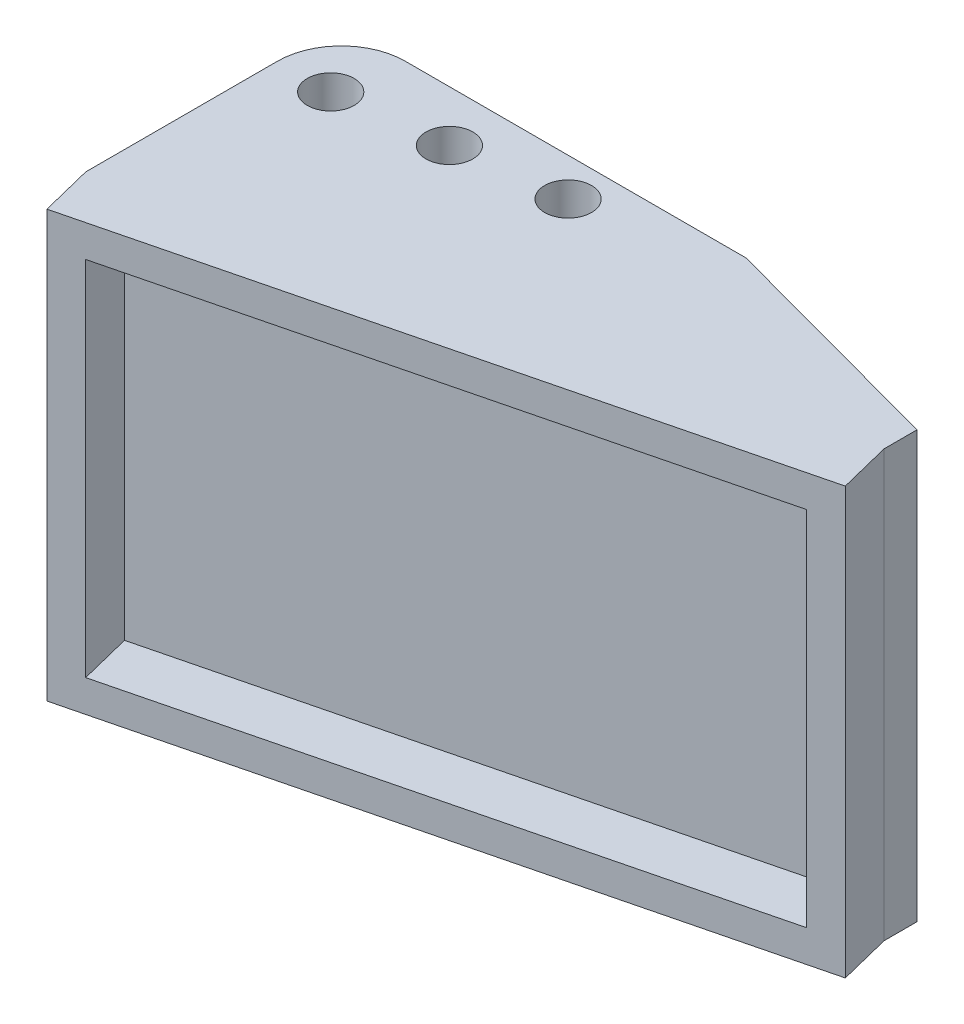
SolidWorks part; units mm, degrees
ref_plane "前视基准面" through (0, 0, 0) normal (0, 0, 1) x (1, 0, 0)
ref_plane "上视基准面" through (0, 0, 0) normal (0, 1, 0) x (1, 0, 0)
ref_plane "右视基准面" through (0, 0, 0) normal (1, 0, 0) x (0, 0, -1)
other "Configuration Table"
sketch "草图1" plane through (0, 0, 0) normal (0, 1, 0) x (1, 0, 0)
  line L0 (-15, -6) -> (15, 1.4798)
  line L1 (-15, 6) -> (15, 6)
  line L2 (-15, 6) -> (-15, -6)
  line L3 (-15, -6) -> (15, -6) construction
  line L4 (15, 6) -> (15, -6) construction
  line L5 (-15, 6) -> (15, -6) construction
  line L6 (-15, -6) -> (15, 6) construction
  line L7 (15, 6) -> (15, 1.4798)
  point P0 (0, 0)
  dimension "D1" = 14
  dimension "D2" = 12
  dimension "D3" = 30
extrude "凸台-拉伸1" add sketch "草图1" along normal blind 20
sketch "草图2" plane through (0, 20, 0) normal (0, 1, 0) x (1, 0, 0)
  line L0 (-15, 6) -> (-15, -6) construction
  line L1 (-12.5, 3) -> (-0.3039, 4.4975) construction
  line L4 (-12.5, 3) -> (-1.0308, 3) construction
  line L5 (15, 6) -> (-15, 6) construction
  circle A1 centre (-12.5, 3) radius 1.1
  circle A2 centre (-7.5373, 3.6093) radius 1.1
  circle A3 centre (-2.5745, 4.2187) radius 1.1
  dimension "D3" = 7
  dimension "D5" = 5
  dimension "D1" = 9
  dimension "D4" = 5
  dimension "D2" = 2.5
sketch "草图3" plane through (0, 0, -6) normal (0, 0, -1) x (-1, 0, 0)
  line L0 (-15, 10) -> (15, 10) construction
  line L1 (-15, 20) -> (-15, 0) construction
  line L2 (15, 20) -> (15, 0) construction
  line L3 (-15, 17.55) -> (15, 17.55)
  line L4 (-15, 2.45) -> (15, 2.45)
  line L5 (-15, 17.55) -> (-15, 2.45)
  line L6 (15, 17.55) -> (15, 2.45)
  dimension "D1" = 7.55
  dimension "D2" = 7.55
extrude "切除-拉伸2" cut sketch "草图2" against normal through all
ref_plane "基准面1" through (0.1676, 0, 0.6724) normal (0.2419, 0, 0.9703) x (0.9703, 0, -0.2419)
extrude "切除-拉伸3" cut sketch "草图3" against normal up to surface (10.4541 mm away) up to plane "基准面1"
fillet "圆角1" radius 3 2 edges at (-15, 1.225, -6) (-15, 18.775, -6)
sketch "草图6" plane through (0.5305, 0, 2.1278) normal (0.2419, 0, 0.9703) x (0.9703, 0, -0.2419)
  line L0 (-14.506, 18.5) -> (-14.506, 1.5)
  line L1 (-14.506, 1.5) -> (13.4124, 1.5)
  line L2 (13.4124, 1.5) -> (13.4124, 18.5)
  line L3 (13.4124, 18.5) -> (-14.506, 18.5)
  line L4 (-16.006, 20) -> (-16.006, 0) construction
  line L5 (14.9124, 20) -> (14.9124, 0) construction
  line L6 (-16.006, 20) -> (14.9124, 20) construction
  line L7 (-16.006, 0) -> (14.9124, 0) construction
  line L9 (-16.006, 20) -> (14.9124, 20)
  line L10 (-16.006, 20) -> (-16.006, 0)
  line L11 (-16.006, 0) -> (14.9124, 0)
  line L12 (14.9124, 20) -> (14.9124, 0)
  dimension "D1" = 1.5
  dimension "D2" = 1.5
  dimension "D3" = 1.5
  dimension "D4" = 1.5
extrude "凸台-拉伸2" add sketch "草图6" along normal blind 2.5
sketch "草图7" plane through (0, 2.45, 0) normal (0, 1, 0) x (1, 0, 0)
  line L0 (15, 3.0258) -> (4, 6)
  line L1 (15, 6) -> (-12, 6) construction
  line L2 (4, 6) -> (15, 6)
  line L3 (15, 3.0258) -> (15, 6) construction
  line L4 (15, 6) -> (15, 3.0258)
  dimension "D1" = 11
extrude "切除-拉伸4" cut sketch "草图7" against normal through all both and the other way through all
